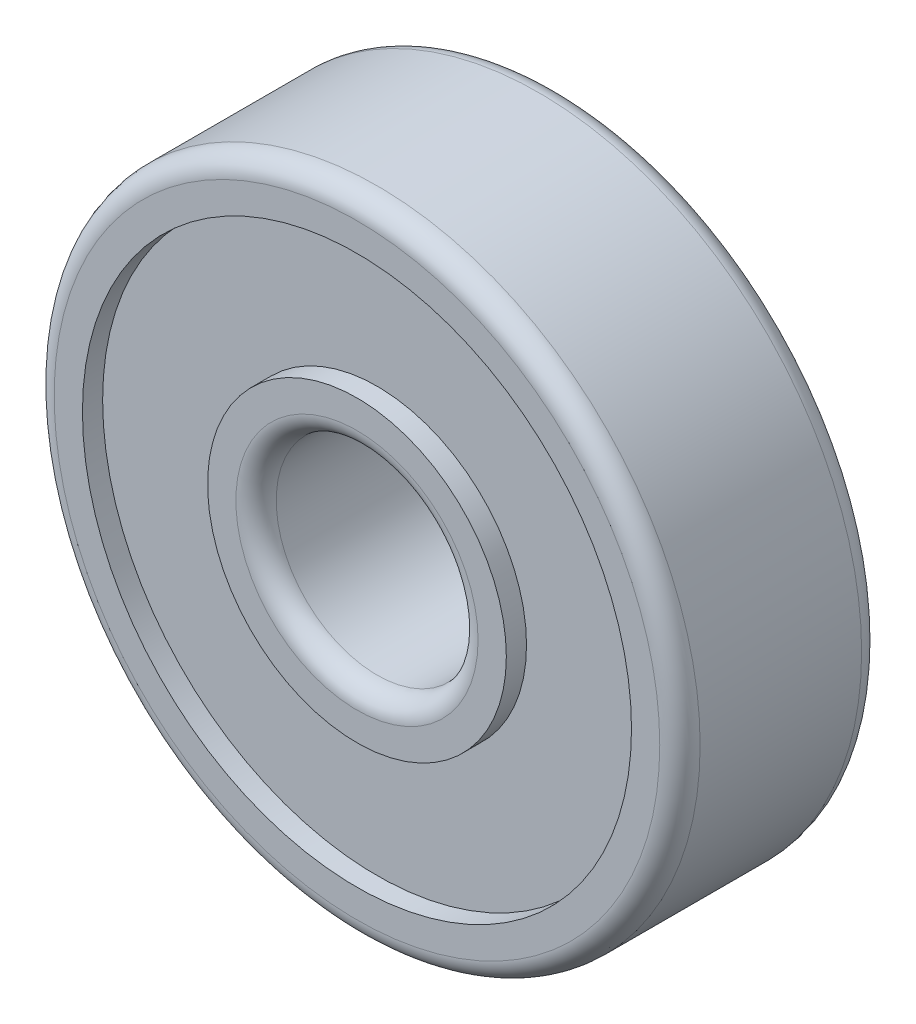
SolidWorks part; units mm, degrees
ref_plane "Plano frontal" through (0, 0, 0) normal (0, 0, 1) x (1, 0, 0)
ref_plane "Plano superior" through (0, 0, 0) normal (0, 1, 0) x (1, 0, 0)
ref_plane "Plano direito" through (0, 0, 0) normal (1, 0, 0) x (0, 0, -1)
sketch "Esboço1" plane through (0, 0, 0) normal (0, 0, 1) x (1, 0, 0)
  circle A0 centre (0, 0) radius 8
  circle A1 centre (0, 0) radius 2.5
  dimension "D1" = 5
  dimension "D2" = 16
extrude "Ressalto-extrusão1" add sketch "Esboço1" along normal blind 5
sketch "Esboço2" plane through (0, 0, 5) normal (0, 0, 1) x (1, 0, 0)
  circle A0 centre (0, 0) radius 3.7
  circle A3 centre (0, 0) radius 2.5 construction
  circle A4 centre (0, 0) radius 6.8
  circle A5 centre (0, 0) radius 8 construction
  dimension "D1" = 1.2
  dimension "D2" = 1.2
extrude "Corte-extrusão1" cut sketch "Esboço2" against normal blind 0.5
sketch "Esboço3" plane through (0, 0, 0) normal (0, 0, -1) x (-1, 0, 0)
  circle A0 centre (0, 0) radius 3.7
  circle A1 centre (0, 0) radius 6.8
  circle A2 centre (0, 0) radius 2.5 construction
  circle A3 centre (0, 0) radius 8 construction
  dimension "D1" = 1.2
  dimension "D2" = 1.2
extrude "Corte-extrusão2" cut sketch "Esboço3" against normal blind 0.5
fillet "Filete1" radius 0.5 4 edges at (8, 0, 0) (8, 0, 5) (2.5, 0, 0) (2.5, 0, 5)
